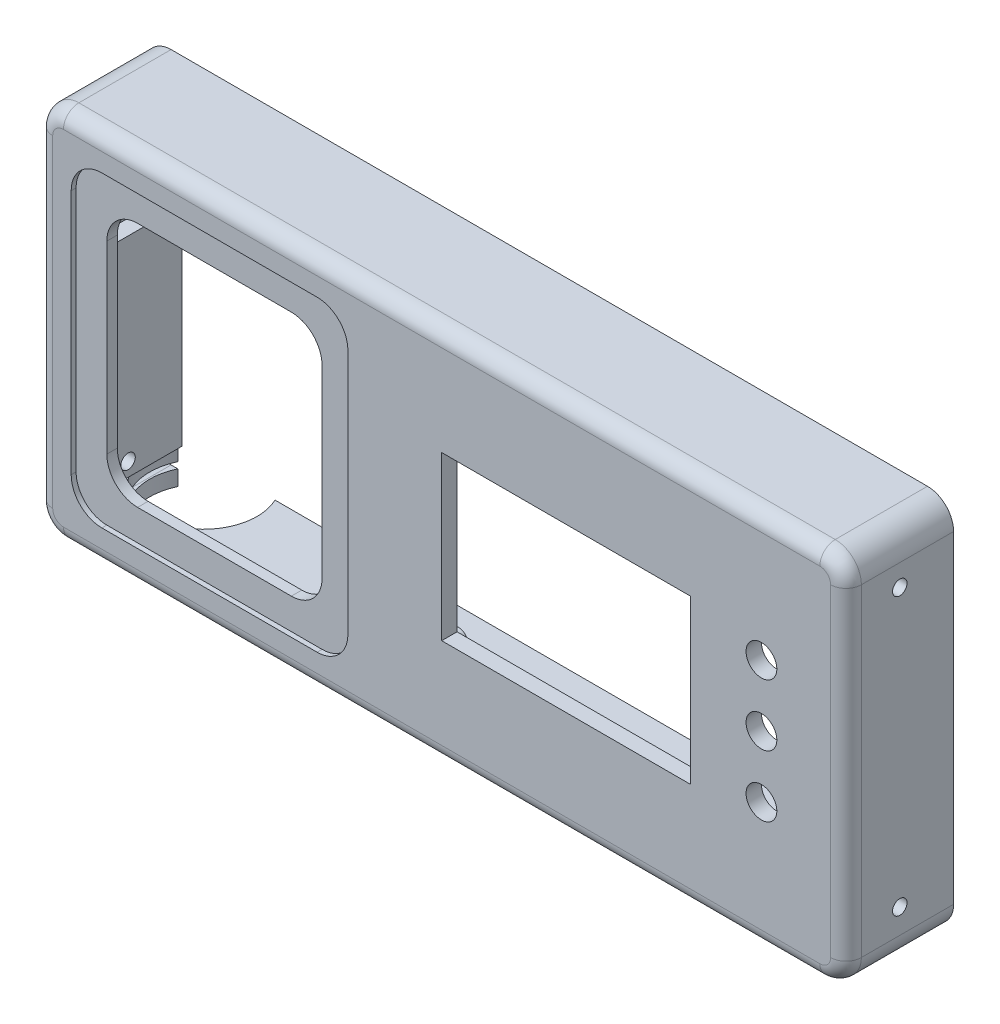
SolidWorks part; units mm, degrees
material "ABS"
ref_plane "Front Plane" through (0, 0, 0) normal (0, 0, 1) x (1, 0, 0)
ref_plane "Top Plane" through (0, 0, 0) normal (0, 1, 0) x (1, 0, 0)
ref_plane "Right Plane" through (0, 0, 0) normal (1, 0, 0) x (0, 0, -1)
sketch "Sketch1" plane through (0, 0, 0) normal (0, 0, 1) x (1, 0, 0)
  line L1 (-124.5, -54) -> (124.5, -54)
  line L2 (-124.5, -54) -> (-124.5, 54)
  line L3 (-124.5, 54) -> (124.5, 54)
  line L4 (124.5, -54) -> (124.5, 54)
  line L5 (-124.5, -54) -> (124.5, 54) construction
  line L6 (-124.5, 54) -> (124.5, -54) construction
  line L7 (119.5, 49) -> (-119.5, 49)
  line L8 (119.5, 49) -> (119.5, -49)
  line L9 (119.5, -49) -> (-119.5, -49)
  line L10 (-119.5, 49) -> (-119.5, -49)
  line L11 (-126.5, -56) -> (126.5, -56)
  line L12 (-126.5, -56) -> (-126.5, 56)
  line L13 (-126.5, 56) -> (126.5, 56)
  line L14 (126.5, -56) -> (126.5, 56)
  line L15 (-126.5, -56) -> (126.5, 56) construction
  line L16 (-126.5, 56) -> (126.5, -56) construction
  line L17 (-131.5, -61) -> (131.5, -61)
  line L18 (-131.5, -61) -> (-131.5, 61)
  line L19 (-131.5, 61) -> (131.5, 61)
  line L20 (131.5, -61) -> (131.5, 61)
  line L21 (-131.5, -61) -> (131.5, 61) construction
  line L22 (-131.5, 61) -> (131.5, -61) construction
  point P0 (0, 0)
  point P10 (0, 0)
  point P15 (0, 0)
  dimension "D1" = 249
  dimension "D2" = 108
  dimension "D3" = 5
  dimension "D4" = 5
  dimension "D5" = 5
  dimension "D6" = 5
  dimension "D7" = 2
  dimension "D8" = 2
  dimension "D9" = 5
  dimension "D10" = 5
extrude "Boss-Extrude1" add sketch "Sketch1" along normal blind 30 contours L17 L20 L19 L18 L14 L11 L12 L13 | L1 L4 L3 L2 L10 L7 L8 L9
sketch "Sketch2" plane through (0, 0, 30) normal (0, 0, 1) x (1, 0, 0)
  line L1 (-131.5, -61) -> (131.5, -61)
  line L2 (-131.5, -61) -> (-131.5, 61)
  line L3 (-131.5, 61) -> (131.5, 61)
  line L4 (131.5, -61) -> (131.5, 61)
  line L5 (-131.5, -61) -> (131.5, 61) construction
  line L6 (-131.5, 61) -> (131.5, -61) construction
  point P0 (0, 0)
extrude "Boss-Extrude2" add sketch "Sketch2" along normal blind 5
fillet "Fillet1" radius 1.5 4 edges at (124.5, -54, 15) (-124.5, -54, 15) (-124.5, 54, 15) (124.5, 54, 15)
sketch "Sketch3" plane through (0, -61, 0) normal (0, -1, 0) x (-1, 0, 0)
  line L1 (131.5, -35) -> (-131.5, -35) construction
  circle A0 centre (105, -7.5) radius 17.5
  circle A1 centre (-105, -7.5) radius 17.5
  dimension "D1" = 105
  dimension "D5" = 35
  dimension "D2" = 105
  dimension "D3" = 27.5
  dimension "D4" = 27.5
extrude "Cut-Extrude1" cut sketch "Sketch3" against normal blind 12
fillet "Fillet2" radius 3.5 4 edges at (126.5, -56, 15) (126.5, 56, 15) (-126.5, 56, 15) (-126.5, -56, 15)
fillet "Fillet3" radius 8.5 4 edges at (-131.5, -61, 17.5) (131.5, -61, 17.5) (131.5, 61, 17.5) (-131.5, 61, 17.5)
fillet "Fillet4" radius 5 8 edges at (129.0104, 58.5104, 35) (131.5, 0, 35) (129.0104, -58.5104, 35) (0, -61, 35) (-129.0104, -58.5104, 35) (-131.5, 0, 35) (-129.0104, 58.5104, 35) (0, 61, 35)
sketch "Sketch4" plane through (131.5, 0, 0) normal (1, 0, 0) x (0, 0, -1)
  line L0 (-35, -61) -> (-35, 61) construction
  line L1 (-35, -61) -> (0, -61) construction
  circle A0 centre (-17.5, -44.5) radius 2.35
  circle A1 centre (-17.5, 45.5) radius 2.35
  dimension "D1" = 17.5
  dimension "D3" = 4.7
  dimension "D4" = 90
  dimension "D2" = 16.5
extrude "Cut-Extrude2" cut sketch "Sketch4" against normal blind 279
sketch "Sketch5" plane through (0, 0, 0) normal (0, 0, -1) x (-1, 0, 0)
  line L0 (123, 54) -> (-123, 54) construction
  line L1 (124.5, 54) -> (104.5, 54)
  line L2 (124.5, 54) -> (124.5, 19)
  line L3 (124.5, 19) -> (104.5, 19)
  line L4 (104.5, 54) -> (104.5, 19)
  line L5 (124.5, -52.5) -> (124.5, 52.5) construction
  line L6 (-124.5, -52.5) -> (-124.5, 52.5) construction
  line L7 (-124.5, 54) -> (-104.5, 54)
  line L8 (-124.5, 54) -> (-124.5, 19)
  line L9 (-124.5, 19) -> (-104.5, 19)
  line L10 (-104.5, 54) -> (-104.5, 19)
  dimension "D1" = 20
  dimension "D2" = 35
  dimension "D3" = 35
  dimension "D4" = 20
extrude "Cut-Extrude3" cut sketch "Sketch5" against normal up to surface (30 mm away) up to face at (0, 0, 30)
sketch "Sketch6" plane through (-126.5, 0, 0) normal (1, 0, 0) x (0, 0, -1)
  line L0 (0, -52.5) -> (0, 52.5) construction
  line L1 (0, 50) -> (-7.5, 50)
  line L2 (0, 50) -> (0, 41)
  line L3 (0, 41) -> (-7.5, 41)
  line L4 (-7.5, 50) -> (-7.5, 41)
  line L6 (0, 35) -> (-22.5, 35)
  line L7 (0, 35) -> (0, 26)
  line L8 (0, 26) -> (-22.5, 26)
  line L9 (-22.5, 35) -> (-22.5, 26)
  circle A1 centre (-17.5, 45.5) radius 2.35 construction
  dimension "D4" = 4.5
  dimension "D5" = 19.5
  dimension "D1" = 7.5
  dimension "D2" = 9
  dimension "D3" = 9
  dimension "D6" = 22.5
extrude "Cut-Extrude4" cut sketch "Sketch6" against normal blind 2.5
sketch "Sketch7" plane through (0, 0, 30) normal (0, 0, 1) x (1, 0, 0)
  line L3 (123, -61) -> (-123, -61) construction
  line L5 (131.5, 52.5) -> (131.5, -52.5) construction
  circle A0 centre (104, 20) radius 5
  circle A1 centre (104, 0) radius 5
  circle A2 centre (104, -20) radius 5
  dimension "D1" = 27.5
  dimension "D4" = 10
  dimension "D2" = 20
  dimension "D3" = 20
  dimension "D5" = 61
extrude "Cut-Extrude8" cut sketch "Sketch7" along normal blind 73.5
sketch "Sketch9" plane through (0, 0, 30) normal (0, 0, -1) x (-1, 0, 0)
  circle A4 centre (-84.5, 32) radius 3
  circle A5 centre (-84.5, -32) radius 3
  circle A6 centre (3.5, -32) radius 3
  circle A7 centre (3.5, 32) radius 3
  circle A8 centre (3.5, 32) radius 1.25
  circle A9 centre (3.5, -32) radius 1.25
  circle A10 centre (-84.5, -32) radius 1.25
  circle A11 centre (-84.5, 32) radius 1.25
  point P25 (0, 0)
  point P26 (0, 0)
  point P27 (0, 0)
  point P28 (0, 0)
  point P29 (0, 0)
  point P30 (0, 0)
  point P31 (0, 0)
  point P32 (92.1791, -35)
  point P33 (93.9221, 35)
  dimension "D1" = 84.5
  dimension "D5" = 6
  dimension "D6" = 2.5
  dimension "D2" = 88
  dimension "D3" = 32
  dimension "D4" = 64
extrude "Boss-Extrude4" add sketch "Sketch9" along normal blind 4
sketch "Sketch10" plane through (0, 0, 30) normal (0, 0, -1) x (-1, 0, 0)
  line L1 (-81, -26.5) -> (0, -26.5)
  line L2 (-81, -26.5) -> (-81, 26.5)
  line L3 (-81, 26.5) -> (0, 26.5)
  line L4 (0, -26.5) -> (0, 26.5)
  line L5 (-81, -26.5) -> (0, 26.5) construction
  line L6 (-81, 26.5) -> (0, -26.5) construction
  point P0 (0, 0)
  dimension "D1" = 81
  dimension "D2" = 53
  dimension "D3" = 0
  dimension "D4" = 26.5
extrude "Cut-Extrude9" cut sketch "Sketch10" against normal blind 13.6
sketch "Sketch11" plane through (0, 0, 35) normal (0, 0, 1) x (1, 0, 0)
  line L0 (-123, -56) -> (123, -56) construction
  line L1 (-120.5, -50) -> (-30.5, -50)
  line L2 (-120.5, -50) -> (-120.5, 50)
  line L3 (-120.5, 50) -> (-30.5, 50)
  line L4 (-30.5, -50) -> (-30.5, 50)
  line L5 (-120.5, -50) -> (-30.5, 50) construction
  line L6 (-120.5, 50) -> (-30.5, -50) construction
  line L10 (-126.5, 52.5) -> (-126.5, -52.5) construction
  point P0 (-75.5, 0)
  dimension "D1" = 90
  dimension "D2" = 100
  dimension "D3" = 56
  dimension "D4" = 6
extrude "Cut-Extrude10" cut sketch "Sketch11" against normal blind 1.6
sketch "Sketch12" plane through (0, 0, 33.4) normal (0, 0, 1) x (1, 0, 0)
  line L0 (-120.5, 50) -> (-120.5, -50) construction
  line L1 (-110.5, 40) -> (-40.5, 40)
  line L2 (-110.5, 40) -> (-110.5, -40)
  line L3 (-110.5, -40) -> (-40.5, -40)
  line L4 (-40.5, 40) -> (-40.5, -40)
  line L5 (-30.5, -50) -> (-30.5, 50) construction
  line L6 (-30.5, 50) -> (-120.5, 50) construction
  line L7 (-120.5, -50) -> (-30.5, -50) construction
  dimension "D1" = 10
  dimension "D2" = 10
  dimension "D3" = 10
  dimension "D4" = 10
extrude "Cut-Extrude11" cut sketch "Sketch12" against normal blind 11.6
fillet "Fillet5" radius 10 8 edges at (-120.5, -50, 34.2) (-30.5, -50, 34.2) (-40.5, -40, 31.7) (-120.5, 50, 34.2) (-110.5, 40, 31.7) (-40.5, 40, 31.7) (-30.5, 50, 34.2) (-110.5, -40, 31.7)
